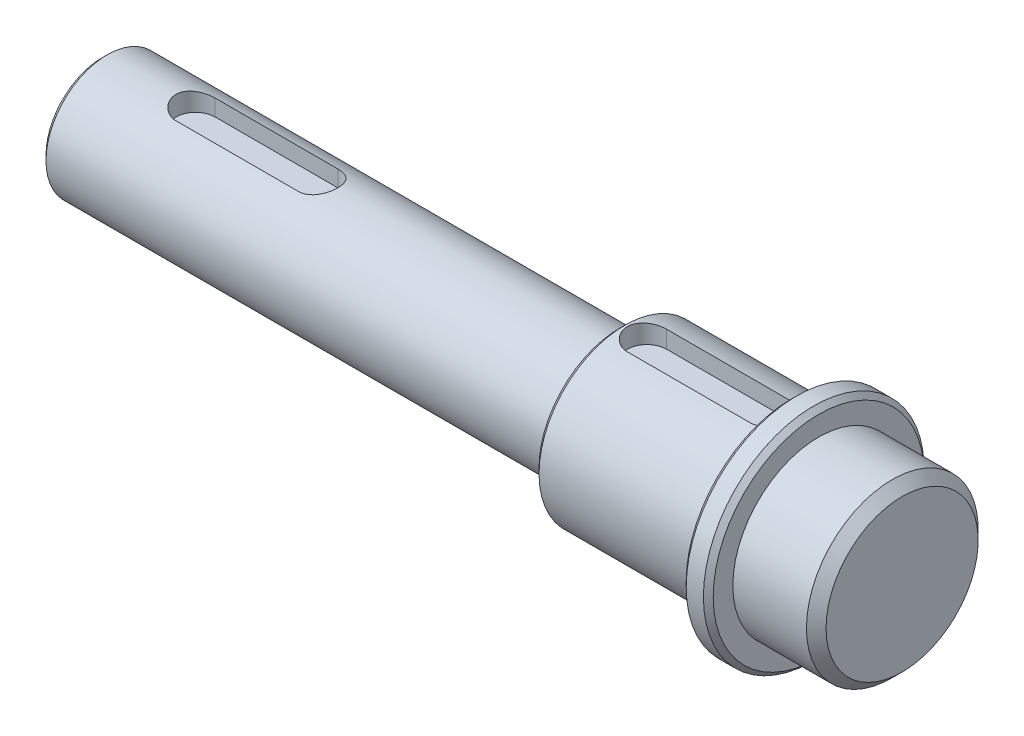
SolidWorks part; units mm, degrees
ref_plane "Front Plane" through (0, 0, 0) normal (0, 0, 1) x (1, 0, 0)
ref_plane "Top Plane" through (0, 0, 0) normal (0, 1, 0) x (1, 0, 0)
ref_plane "Right Plane" through (0, 0, 0) normal (1, 0, 0) x (0, 0, -1)
sketch "Sketch1" plane through (0, 0, 0) normal (0, 0, 1) x (1, 0, 0)
  line L0 (-79.2891, 0) -> (90.237, 0) construction
  line L1 (-63.0431, 0) -> (-63.0431, 12.4832)
  line L2 (-19.5431, 17.5) -> (14.4569, 17.5)
  line L3 (36.9569, 15.5) -> (36.9569, 0)
  line L4 (14.4569, 17.5) -> (14.4569, 21.5)
  line L5 (15.4569, 22.5) -> (18.9569, 22.5)
  line L6 (19.9569, 21.5) -> (19.9569, 17.5)
  line L7 (-19.5431, 17.5) -> (-20.5447, 16.5)
  line L8 (14.4569, 21.5) -> (15.4569, 22.5)
  line L9 (18.9569, 22.5) -> (19.9569, 21.5)
  line L10 (19.9569, 17.5) -> (34.9569, 17.5)
  line L11 (34.9569, 17.5) -> (36.9569, 15.5)
  line L12 (-63.0431, 0) -> (36.9569, 0)
  line L14 (-20.5447, 16.5) -> (-20.5512, 12.4832)
  line L15 (-63.0431, 12.4832) -> (-20.5512, 12.4832)
  point P4 (-63.0431, 17.5)
  point P5 (-46.0431, 17.5)
  point P6 (36.9569, 17.5)
  point P8 (-3.0431, 17.5)
  point P9 (-20.5431, 17.5)
  point P10 (14.4569, 17.5)
  point P11 (19.9569, 17.5)
  point P13 (14.4569, 22.5)
  point P15 (19.9569, 22.5)
  point P18 (-20.5431, 17.5)
  point P27 (-63.0431, 12.4832)
  point P29 (0, 0)
  point P30 (-63.0431, 12.5)
  point P31 (-62.9623, 12.4933)
  dimension "D1" = 17.5
  dimension "D2" = 100
  dimension "D3" = 17
  dimension "D4" = 60
  dimension "D5" = 42.5
  dimension "D6" = 77.5
  dimension "D7" = 17
  dimension "D8" = 5
revolve "Revolve1" add sketch "Sketch1" angle 360 about L0
ref_plane "Plane1" through (0, 17.5, 0) normal (0, 1, 0) x (1, 0, 0)
sketch "Sketch2" plane through (0, 17.5, 0) normal (0, 1, 0) x (1, 0, 0)
  line L3 (-15.0332, 0) -> (9.9668, 0) construction
  line L4 (-15.0332, 4) -> (9.9668, 4)
  line L5 (-15.0332, -4) -> (9.9668, -4)
  arc A0 (-15.0332, 4) -> (-15.0332, -4) centre (-15.0332, 0) ccw
  arc A1 (9.9668, -4) -> (9.9668, 4) centre (9.9668, 0) ccw
  point P8 (-2.5332, 0)
  dimension "D1" = 25
  dimension "D3" = 8
extrude "Cut-Extrude1" cut sketch "Sketch2" against normal blind 4
sketch "Sketch3" plane through (-63.0431, 0, 0) normal (-1, 0, 0) x (0, 0, 1)
  circle A1 centre (0, 0) radius 12.4832
  circle A2 centre (0, 0) radius 12.4832
  dimension "D1" = 0
extrude "Boss-Extrude1" add sketch "Sketch3" along normal blind 63
ref_plane "Plane2" through (0, 12.4832, 0) normal (0, 1, 0) x (1, 0, 0)
sketch "Sketch4" plane through (0, 12.4832, 0) normal (0, 1, 0) x (1, 0, 0)
  line L3 (-107.0431, 4) -> (-82.0431, 4)
  line L4 (-107.0431, -4) -> (-82.0431, -4)
  arc A0 (-107.0431, 4) -> (-107.0431, -4) centre (-107.0431, 0) ccw
  arc A1 (-82.0431, -4) -> (-82.0431, 4) centre (-82.0431, 0) ccw
  point P7 (-94.5431, 0)
  dimension "D2" = 25
  dimension "D3" = 8
extrude "Cut-Extrude2" cut sketch "Sketch4" against normal blind 4
chamfer "Chamfer1" distance 1 angle 45 1 edges at (-126.0431, 0, 12.4832)
